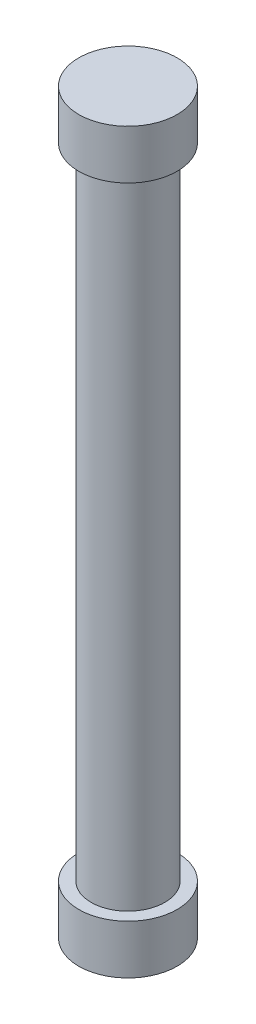
SolidWorks part; units mm, degrees
ref_plane "Front Plane" through (0, 0, 0) normal (0, 0, 1) x (1, 0, 0)
ref_plane "Top Plane" through (0, 0, 0) normal (0, 1, 0) x (1, 0, 0)
ref_plane "Right Plane" through (0, 0, 0) normal (1, 0, 0) x (0, 0, -1)
sketch "Sketch2" plane through (0, 0, 0) normal (1, 0, 0) x (0, 0, -1)
  line L0 (0.9891, 27.3315) -> (0.9891, -2.6685)
  line L1 (0.9891, -2.6685) -> (-1.0109, -2.6685)
  line L2 (-1.0109, -2.6685) -> (-1.0109, -0.6685)
  line L3 (-1.0109, -0.6685) -> (-0.5109, -0.6685)
  line L4 (-0.5109, -0.6685) -> (-0.5109, 25.3315)
  line L5 (-0.5109, 25.3315) -> (-1.0109, 25.3315)
  line L6 (-1.0109, 25.3315) -> (-1.0109, 27.3315)
  line L7 (-1.0109, 27.3315) -> (0.9891, 27.3315)
  point P3 (0, 2.2718)
  dimension "D1" = 2
  dimension "D2" = 2
  dimension "D3" = 1.5
  dimension "D4" = 2
  dimension "D5" = 2
  dimension "D6" = 30
revolve "Revolve1" add sketch "Sketch2" angle 360 about L0
